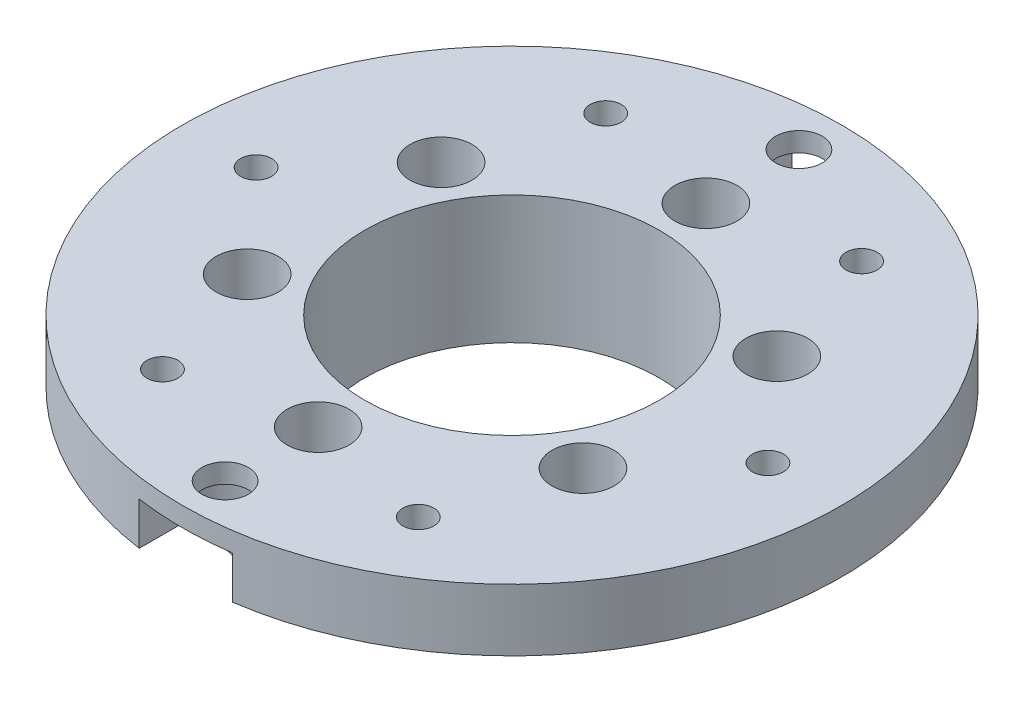
SolidWorks part; units mm, degrees
material "Like ABS"
ref_plane "Front Plane" through (0, 0, 0) normal (0, 0, 1) x (1, 0, 0)
ref_plane "Top Plane" through (0, 0, 0) normal (0, 1, 0) x (1, 0, 0)
ref_plane "Right Plane" through (0, 0, 0) normal (1, 0, 0) x (0, 0, -1)
sketch "Sketch1" plane through (0, 0, 0) normal (0, 1, 0) x (1, 0, 0)
  circle A0 centre (0, 0) radius 21.25
  dimension "D1" = 42.5
extrude "Boss-Extrude1" add sketch "Sketch1" along normal blind 4
sketch "Sketch2" plane through (0, 4, 0) normal (0, 1, 0) x (1, 0, 0)
  line L0 (0, 0) -> (0, 18.5) construction
  circle A0 centre (0, 18.5) radius 1.5
  dimension "D2" = 3
  dimension "D1" = 18.5
extrude "Cut-Extrude1" cut sketch "Sketch2" against normal up to surface (4 mm away) up to face at (0, 0, 21.25)
sketch "Sketch5" plane through (0, 0, 0) normal (0, -1, 0) x (1, 0, 0)
  circle A0 centre (0, 0) radius 16.5
  dimension "D1" = 33
extrude "Boss-Extrude2" add sketch "Sketch5" along normal blind 0.25
sketch "Sketch6" plane through (0, -0.25, 0) normal (0, -1, 0) x (1, 0, 0)
  circle A0 centre (0, 0) radius 15.075
  dimension "D1" = 30.15
extrude "Boss-Extrude3" add sketch "Sketch6" along normal blind 4
chamfer "Chamfer1" distance 0.5 angle 45 1 edges at (0, -4.25, -15.075)
sketch "Sketch7" plane through (0, -4.25, 0) normal (0, -1, 0) x (1, 0, 0)
  circle A0 centre (0, 0) radius 9.5
  dimension "D1" = 19
extrude "Cut-Extrude3" cut sketch "Sketch7" against normal up to surface (8.25 mm away) up to face at (0, 4, -17)
sketch "Sketch8" plane through (0, 4, 0) normal (0, 1, 0) x (1, 0, 0)
  line L0 (0, 16.5) -> (0, 0) construction
  line L1 (0, 0) -> (8.25, 14.2894) construction
  circle A0 centre (8.25, 14.2894) radius 1
  dimension "D2" = 2
  dimension "D1" = 30
  dimension "D3" = 16.5
extrude "Cut-Extrude4" cut sketch "Sketch8" against normal blind 3
pattern_circular "CirPattern2" count 6 over 360 about axis through (0, 0, 0) along (0, 1, 0) of "Cut-Extrude4"
sketch "Sketch11" plane through (0, -0.25, 0) normal (0, -1, 0) x (1, 0, 0)
  line L2 (-3, -18.5) -> (-3, -22.8837)
  line L3 (-3, -22.8837) -> (3, -22.8837)
  line L4 (3, -18.5) -> (3, -22.8837)
  arc A0 (3, -18.5) -> (-3, -18.5) centre (0, -18.5) ccw
  dimension "D1" = 6
extrude "Cut-Extrude5" cut sketch "Sketch11" against normal blind 3
pattern_circular "CirPattern3" count 2 over 360 about axis through (0, 0, 0) along (0, 1, 0) of "Cut-Extrude1", "Cut-Extrude5"
sketch "Sketch13" plane through (0, 4, 0) normal (0, 1, 0) x (1, 0, 0)
  line L0 (0, 0) -> (0, 12.5) construction
  circle A0 centre (0, 12.5) radius 2
  dimension "D1" = 4
  dimension "D2" = 12.5
extrude "Cut-Extrude6" cut sketch "Sketch13" against normal blind 6.25
sketch "Sketch14" plane through (0, -2.25, 0) normal (0, 1, 0) x (1, 0, 0)
  circle A0 centre (0, 12.5) radius 1.6
  dimension "D1" = 3.2
extrude "Cut-Extrude7" cut sketch "Sketch14" against normal up to surface (2 mm away) up to face at (0, -4.25, -9.5)
pattern_circular "CirPattern4" count 6 over 360 about axis through (0, 0, 0) along (0, 1, 0) of "Cut-Extrude7", "Cut-Extrude6"
